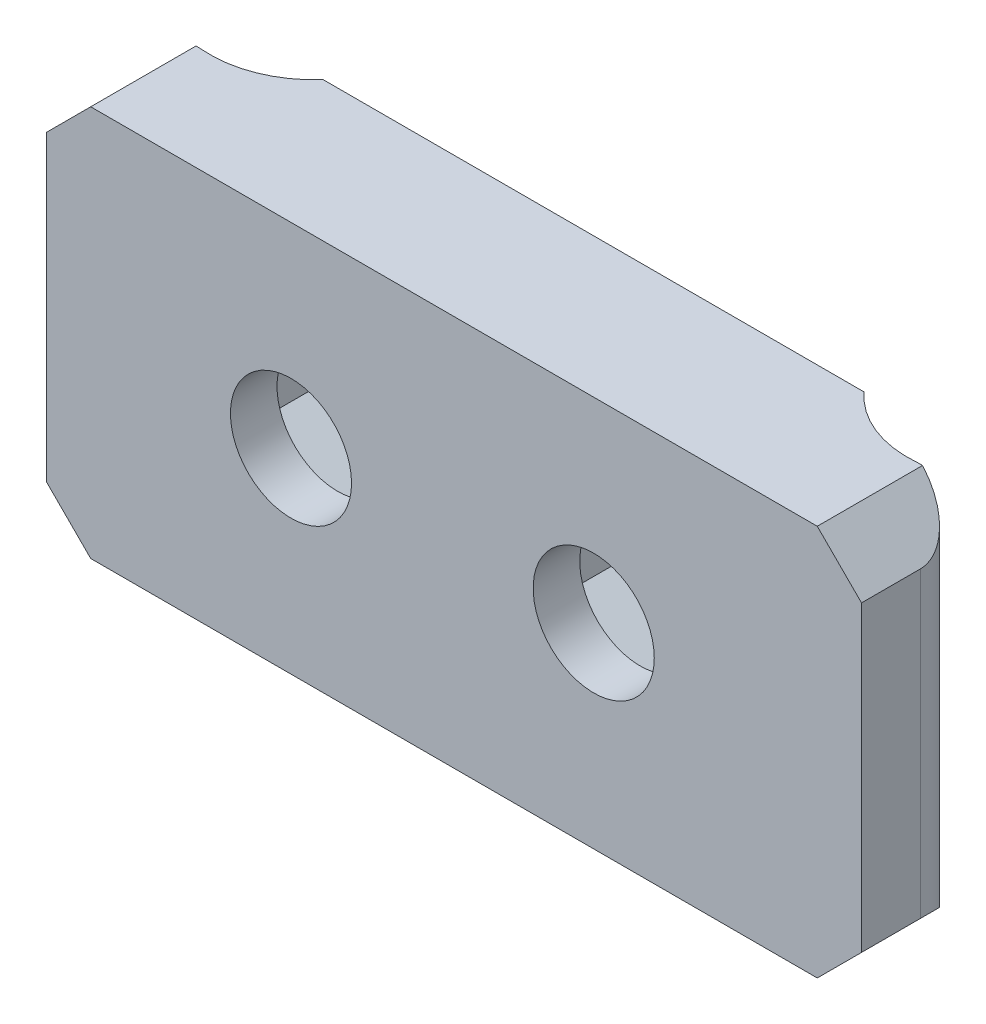
SolidWorks part; units mm, degrees
ref_plane "Front Plane" through (0, 0, 0) normal (0, 0, 1) x (1, 0, 0)
ref_plane "Top Plane" through (0, 0, 0) normal (0, 1, 0) x (1, 0, 0)
ref_plane "Right Plane" through (0, 0, 0) normal (1, 0, 0) x (0, 0, -1)
sketch "Sketch1" plane through (0, 0, 789.6201) normal (0, 0, -1) x (-1, 0, 0)
  line L1 (-51.7892, -203.5647) -> (-55.8892, -205.9318)
  line L2 (-55.8892, -205.9318) -> (-55.8892, -210.6661)
  line L3 (-55.8892, -210.6661) -> (-51.7892, -213.0332)
  line L4 (-51.7892, -213.0332) -> (-47.6892, -210.6661)
  line L5 (-47.6892, -210.6661) -> (-47.6892, -205.9318)
  line L6 (-47.6892, -205.9318) -> (-51.7892, -203.5647)
  line L7 (-28.2892, -204.7989) -> (-28.2892, -222.7989) construction
  line L8 (-42.8892, -205.9318) -> (-42.8892, -210.6661)
  line L9 (-42.8892, -210.6661) -> (-38.7892, -213.0332)
  line L10 (-38.7892, -213.0332) -> (-34.6892, -210.6661)
  line L11 (-34.6892, -210.6661) -> (-34.6892, -205.9318)
  line L12 (-34.6892, -205.9318) -> (-38.7892, -203.5647)
  line L13 (-38.7892, -203.5647) -> (-42.8892, -205.9318)
  line L14 (-63.2892, -197.7989) -> (-28.2892, -197.7989)
  line L15 (-63.2892, -197.7989) -> (-63.2892, -218.7989)
  line L16 (-63.2892, -218.7989) -> (-28.2892, -218.7989)
  line L17 (-28.2892, -197.7989) -> (-28.2892, -218.7989)
  circle A0 centre (-51.7892, -208.2989) radius 4.1 construction
  circle A1 centre (-38.7892, -208.2989) radius 4.1 construction
  dimension "D1" = 8.2
  dimension "D2" = 10.5
  dimension "D3" = 8.2
  dimension "D4" = 0
extrude "Boss-Extrude1" add sketch "Sketch1" along normal blind 6
sketch "Sketch2" plane through (0, 0, 789.6201) normal (0, 0, 1) x (1, 0, 0)
  line L1 (28.2892, -197.7989) -> (63.2892, -197.7989)
  line L2 (28.2892, -197.7989) -> (28.2892, -218.7989)
  line L3 (28.2892, -218.7989) -> (63.2892, -218.7989)
  line L4 (63.2892, -197.7989) -> (63.2892, -218.7989)
  circle A0 centre (38.7892, -208.2989) radius 2.6
  circle A1 centre (51.7892, -208.2989) radius 2.6
  dimension "D1" = 5.2
  dimension "D2" = 5.2
  dimension "D3" = 13
extrude "Boss-Extrude2" add sketch "Sketch2" against normal blind 2
chamfer "Chamfer1" distance 4 angle 45 4 edges at (63.2892, -197.7989, 786.6201) (28.2892, -197.7989, 786.6201) (28.2892, -218.7989, 786.6201) (63.2892, -218.7989, 786.6201)
chamfer "Chamfer2" distance 0.5 angle 45 20 edges at (40.8392, -211.8496, 783.6201) (36.7392, -211.8496, 783.6201) (34.6892, -208.2989, 783.6201) (36.7392, -204.7482, 783.6201) (40.8392, -204.7482, 783.6201) (42.8892, -208.2989, 783.6201) (55.8892, -208.2989, 783.6201) (53.8392, -211.8496, 783.6201) (49.7392, -211.8496, 783.6201) (47.6892, -208.2989, 783.6201) (49.7392, -204.7482, 783.6201) (53.8392, -204.7482, 783.6201) (30.2892, -199.7989, 783.6201) (28.2892, -208.2989, 783.6201) (30.2892, -216.7989, 783.6201) (45.7892, -218.7989, 783.6201) (61.2892, -216.7989, 783.6201) (63.2892, -208.2989, 783.6201) (61.2892, -199.7989, 783.6201) (45.7892, -197.7989, 783.6201)
sketch "Sketch3" plane through (0, -197.7989, 0) normal (0, 1, 0) x (1, 0, 0)
  line L4 (45.7892, -783.6201) -> (45.7892, -789.6201) construction
  line L5 (32.4963, -783.6201) -> (59.082, -783.6201) construction
  line L6 (32.2892, -789.6201) -> (59.2892, -789.6201) construction
  circle A3 centre (30.8222, -780.6201) radius 4.5
  circle A4 centre (60.7561, -780.6201) radius 4.5
  dimension "D1" = 9
extrude "Cut-Extrude1" cut sketch "Sketch3" against normal blind 49.5
fillet "Fillet1" radius 2 2 edges at (30.2258, -199.8623, 785.0805) (28.2892, -208.2989, 784.3395)
fillet "Fillet2" radius 2 2 edges at (61.3525, -216.7356, 785.0805) (63.2892, -208.2989, 784.3395)
sketch "Sketch5" plane through (0, 0, 783.6201) normal (0, 0, -1) x (-1, 0, 0)
  line L0 (-57.9277, -197.7989) -> (-33.6506, -197.7989) construction
  line L1 (-65.6909, -193.7064) -> (-26.4716, -193.7064)
  line L2 (-65.6909, -193.7064) -> (-65.6909, -199.8989)
  line L3 (-65.6909, -199.8989) -> (-26.4716, -199.8989)
  line L4 (-26.4716, -193.7064) -> (-26.4716, -199.8989)
  line L5 (-26.4716, -224.7999) -> (-64.3667, -224.7999)
  line L6 (-26.4716, -224.7999) -> (-26.4716, -216.6989)
  line L7 (-26.4716, -216.6989) -> (-64.3667, -216.6989)
  line L8 (-64.3667, -224.7999) -> (-64.3667, -216.6989)
  line L9 (-33.6506, -218.7989) -> (-57.9277, -218.7989) construction
  dimension "D1" = 2.1
  dimension "D2" = 2.1
extrude "Cut-Extrude2" cut sketch "Sketch5" against normal blind 10
